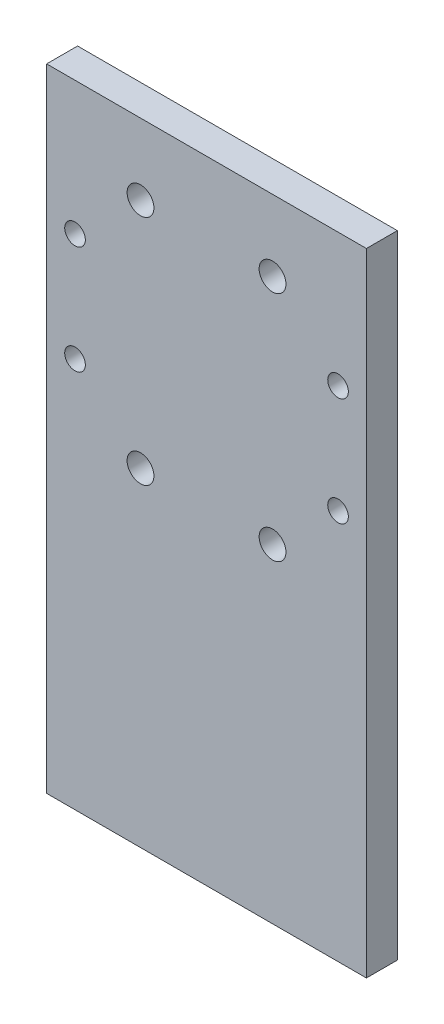
SolidWorks part; units mm, degrees
ref_plane "前视基准面" through (0, 0, 0) normal (0, 0, 1) x (1, 0, 0)
ref_plane "上视基准面" through (0, 0, 0) normal (0, 1, 0) x (1, 0, 0)
ref_plane "右视基准面" through (0, 0, 0) normal (1, 0, 0) x (0, 0, -1)
other "Configuration Table"
sketch "草图1" plane through (0, 0, 0) normal (0, 0, 1) x (1, 0, 0)
  line L0 (0, 74.725) -> (0, -66.9152) construction
  line L1 (-31, 61.25) -> (31, 61.25)
  line L2 (-31, 61.25) -> (-31, -61.25)
  line L3 (-31, -61.25) -> (31, -61.25)
  line L4 (31, 61.25) -> (31, -61.25)
  line L5 (-31, 61.25) -> (31, -61.25) construction
  line L6 (-31, -61.25) -> (31, 61.25) construction
  line L7 (-25.5, 35.45) -> (-25.5, 14.45) construction
  line L8 (-25.5, 24.95) -> (0, 24.95) construction
  circle A0 centre (-25.5, 35.45) radius 2
  circle A1 centre (-25.5, 14.45) radius 2
  circle A2 centre (25.5, 14.45) radius 2
  circle A3 centre (25.5, 35.45) radius 2
  circle A4 centre (-12.8, 47.45) radius 2.6
  circle A5 centre (12.8, 47.45) radius 2.6
  circle A6 centre (12.8, 2.45) radius 2.6
  circle A7 centre (-12.8, 2.45) radius 2.6
  point P0 (0, 0)
  dimension "D3" = 4
  dimension "D7" = 5.2
  dimension "D1" = 62
  dimension "D2" = 122.5
  dimension "D4" = 51
  dimension "D5" = 21
  dimension "D6" = 12
  dimension "D8" = 12.7
  dimension "D9" = 25.8
extrude "凸台-拉伸1" add sketch "草图1" along normal blind 6
